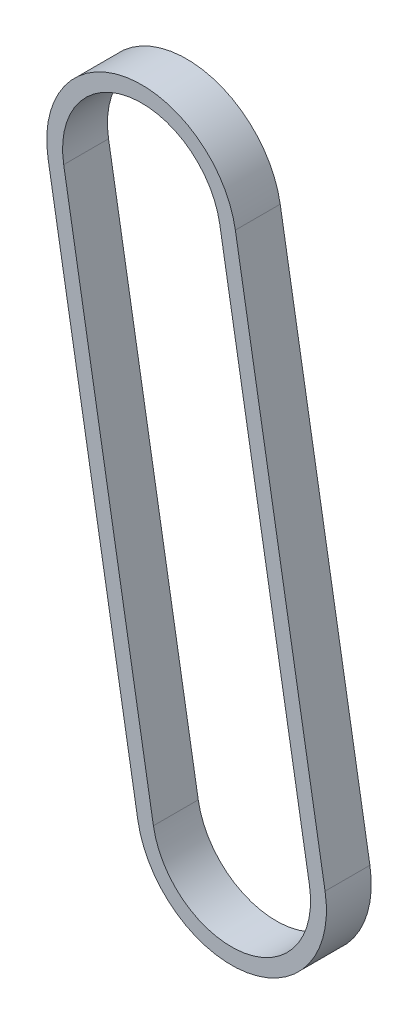
SolidWorks part; units mm, degrees
material "天然橡胶"
ref_plane "前视基准面" through (0, 0, 0) normal (0, 0, 1) x (1, 0, 0)
ref_plane "上视基准面" through (0, 0, 0) normal (0, 1, 0) x (1, 0, 0)
ref_plane "右视基准面" through (0, 0, 0) normal (1, 0, 0) x (0, 0, -1)
sketch "草图1" plane through (0, 0, 0) normal (0, 0, 1) x (1, 0, 0)
  line L0 (0, 62.5904) -> (0, -37.4096) construction
  line L1 (-2.2122, 65.1043) -> (14.7878, -34.8957)
  line L2 (-31.7878, 60.0764) -> (-14.7878, -39.9236)
  line L3 (-34.7454, 59.5736) -> (-17.7454, -40.4264)
  line L4 (0.7454, 65.6071) -> (17.7454, -34.3929)
  line L5 (0, 62.5904) -> (-17, 62.5904) construction
  arc A0 (-2.2122, 65.1043) -> (-31.7878, 60.0764) centre (-17, 62.5904) ccw
  arc A1 (-14.7878, -39.9236) -> (14.7878, -34.8957) centre (0, -37.4096) ccw
  arc A2 (0.7454, 65.6071) -> (-34.7454, 59.5736) centre (-17, 62.5904) ccw
  arc A3 (-17.7454, -40.4264) -> (17.7454, -34.3929) centre (0, -37.4096) ccw
  dimension "D1" = 30
  dimension "D2" = 30
  dimension "D3" = 100
  dimension "D5" = 17
  dimension "D4" = 3
extrude "凸台-拉伸1" add sketch "草图1" along normal blind 8.5
